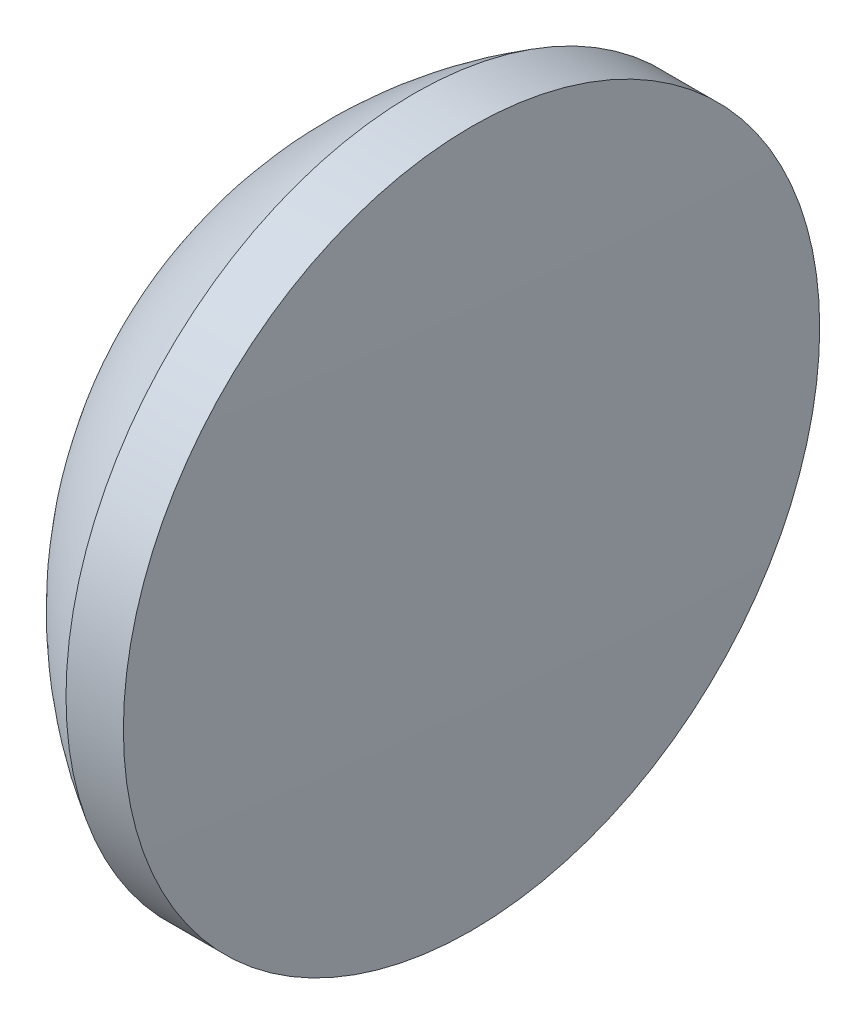
SolidWorks part; units mm, degrees
ref_plane "前视基准面" through (0, 0, 0) normal (0, 0, 1) x (1, 0, 0)
ref_plane "上视基准面" through (0, 0, 0) normal (0, 1, 0) x (1, 0, 0)
ref_plane "右视基准面" through (0, 0, 0) normal (1, 0, 0) x (0, 0, -1)
sketch "草图1" plane through (0, 0, 0) normal (0, 0, 1) x (1, 0, 0)
  line L1 (-1.009, 1.7601) -> (-0.719, 1.7601)
  line L2 (-1.009, -1.7601) -> (-0.719, -1.7601)
  line L3 (-2.0288, 0) -> (-0.6952, 0) construction
  arc A0 (-1.009, 1.7601) -> (-1.009, -1.7601) centre (0, 0) ccw
  arc A1 (-0.719, -1.7601) -> (-0.719, 1.7601) centre (-65.9512, 0) ccw
  point P6 (-0.6952, 0)
  point P8 (-2.0288, 0)
  dimension "D1" = 1.7601
  dimension "D2" = 1.3336
revolve "旋转1" add sketch "草图1" angle 360 about L3
